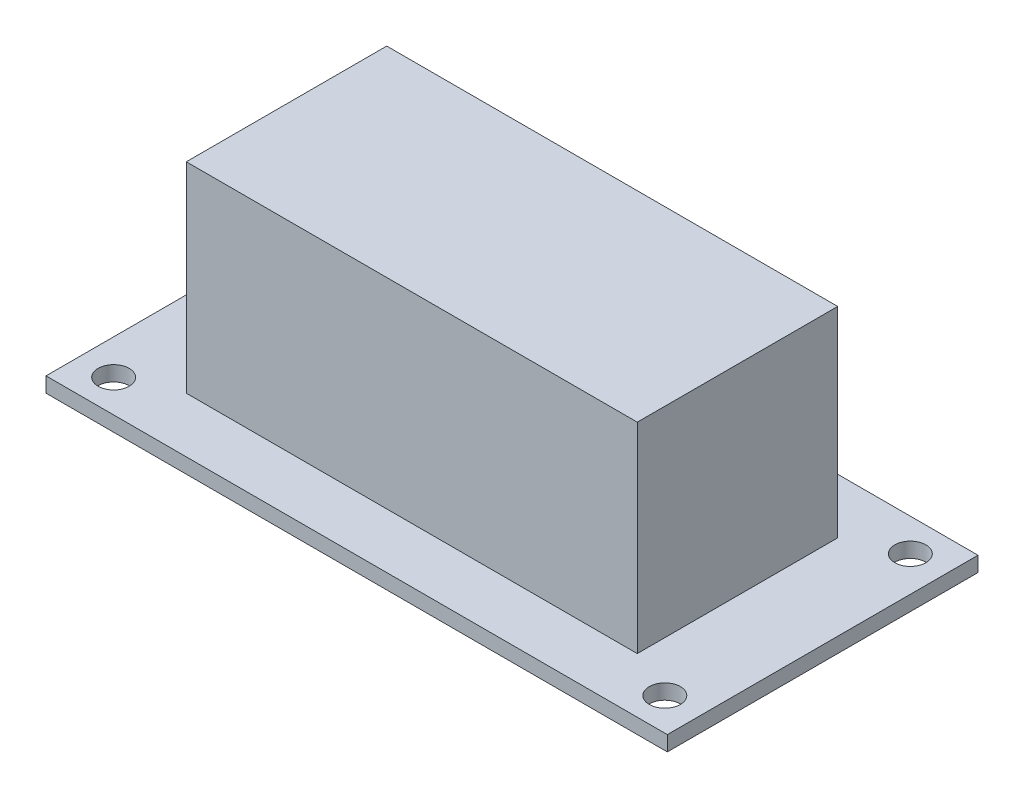
SolidWorks part; units mm, degrees
ref_plane "前基準面" through (0, 0, 0) normal (0, 0, 1) x (1, 0, 0)
ref_plane "上基準面" through (0, 0, 0) normal (0, 1, 0) x (1, 0, 0)
ref_plane "右基準面" through (0, 0, 0) normal (1, 0, 0) x (0, 0, -1)
sketch "草圖1" plane through (0, 0, 0) normal (0, 1, 0) x (1, 0, 0)
  line L1 (-31, -15.5) -> (31, -15.5)
  line L2 (-31, -15.5) -> (-31, 15.5)
  line L3 (-31, 15.5) -> (31, 15.5)
  line L4 (31, -15.5) -> (31, 15.5)
  line L5 (-31, -15.5) -> (31, 15.5) construction
  line L6 (-31, 15.5) -> (31, -15.5) construction
  line L7 (-27.5, -12.25) -> (27.5, -12.25) construction
  line L8 (-27.5, -12.25) -> (-27.5, 12.25) construction
  line L9 (-27.5, 12.25) -> (27.5, 12.25) construction
  line L10 (27.5, -12.25) -> (27.5, 12.25) construction
  line L11 (-27.5, -12.25) -> (27.5, 12.25) construction
  line L12 (-27.5, 12.25) -> (27.5, -12.25) construction
  circle A0 centre (-27.5, 12.25) radius 1.55
  circle A1 centre (27.5, 12.25) radius 1.55
  circle A2 centre (27.5, -12.25) radius 1.55
  circle A3 centre (-27.5, -12.25) radius 1.55
  point P0 (0, 0)
  point P6 (0, 0)
  dimension "D5" = 3.1
  dimension "D1" = 62
  dimension "D2" = 31
  dimension "D3" = 55
  dimension "D4" = 24.5
extrude "填料-伸長1" add sketch "草圖1" along normal blind 1.5
sketch "草圖2" plane through (0, 1.5, 0) normal (0, 1, 0) x (1, 0, 0)
  line L1 (-22.5, -10) -> (22.5, -10)
  line L2 (-22.5, -10) -> (-22.5, 10)
  line L3 (-22.5, 10) -> (22.5, 10)
  line L4 (22.5, -10) -> (22.5, 10)
  line L5 (-22.5, -10) -> (22.5, 10) construction
  line L6 (-22.5, 10) -> (22.5, -10) construction
  point P0 (0, 0)
  dimension "D1" = 45
  dimension "D2" = 20
extrude "填料-伸長2" add sketch "草圖2" along normal blind 20
